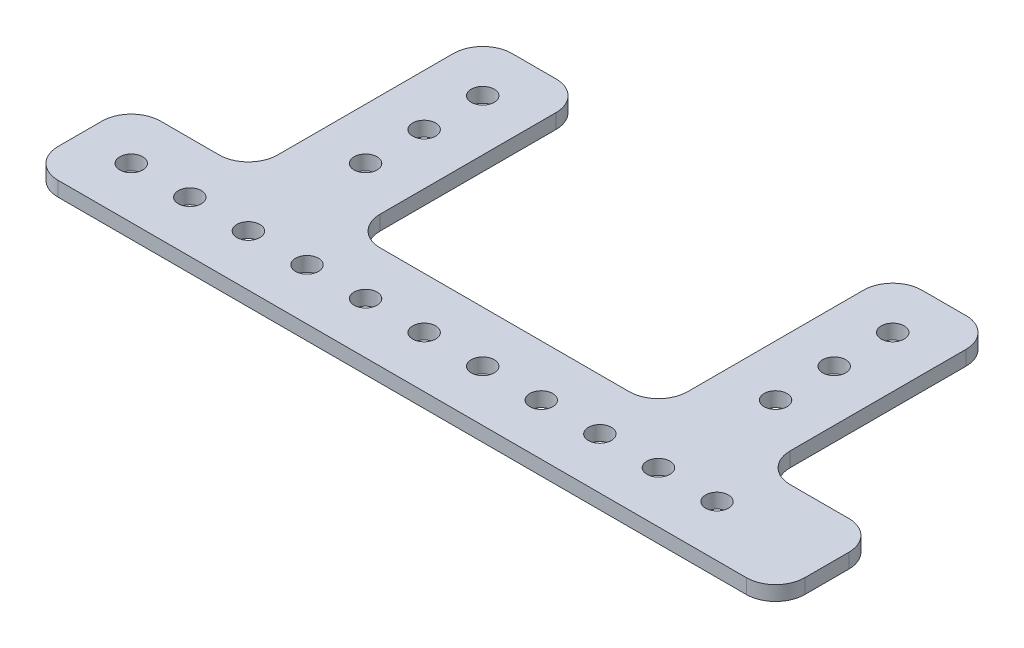
SolidWorks part; units mm, degrees
material "6061-T6 (SS)"
ref_plane "Front Plane" through (0, 0, 0) normal (0, 0, 1) x (1, 0, 0)
ref_plane "Top Plane" through (0, 0, 0) normal (0, 1, 0) x (1, 0, 0)
ref_plane "Right Plane" through (0, 0, 0) normal (1, 0, 0) x (0, 0, -1)
sketch "Sketch1" plane through (0, 0, 0) normal (0, 1, 0) x (1, 0, 0)
  line L0 (-82.55, 0) -> (82.55, 0)
  line L1 (82.55, 0) -> (82.55, 25.4)
  line L2 (82.55, 25.4) -> (57.15, 25.4)
  line L3 (57.15, 25.4) -> (57.15, 76.2)
  line L4 (57.15, 76.2) -> (31.75, 76.2)
  line L5 (31.75, 76.2) -> (31.75, 25.4)
  line L6 (31.75, 25.4) -> (-31.75, 25.4)
  line L7 (-31.75, 25.4) -> (-31.75, 76.2)
  line L8 (-31.75, 76.2) -> (-57.15, 76.2)
  line L9 (-57.15, 76.2) -> (-57.15, 25.4)
  line L10 (-57.15, 25.4) -> (-82.55, 25.4)
  line L11 (-82.55, 25.4) -> (-82.55, 0)
  line L12 (-82.55, 12.7) -> (82.55, 12.7) construction
  line L13 (-69.85, 12.7) -> (-57.15, 12.7) construction
  line L14 (-44.45, 76.2) -> (-44.45, 0) construction
  line L15 (-44.45, 38.1) -> (-44.45, 50.8) construction
  line L16 (0, 0) -> (0, 25.4) construction
  line L17 (-55.5625, 74.6125) -> (-55.5625, 23.8125)
  line L18 (-55.5625, 23.8125) -> (-80.9625, 23.8125)
  line L19 (-80.9625, 23.8125) -> (-80.9625, 1.5875)
  line L20 (-80.9625, 1.5875) -> (80.9625, 1.5875)
  line L21 (80.9625, 1.5875) -> (80.9625, 23.8125)
  line L22 (80.9625, 23.8125) -> (55.5625, 23.8125)
  line L23 (55.5625, 23.8125) -> (55.5625, 74.6125)
  line L24 (55.5625, 74.6125) -> (33.3375, 74.6125)
  line L25 (33.3375, 74.6125) -> (33.3375, 23.8125)
  line L26 (33.3375, 23.8125) -> (-33.3375, 23.8125)
  line L27 (-33.3375, 23.8125) -> (-33.3375, 74.6125)
  line L28 (-33.3375, 74.6125) -> (-55.5625, 74.6125)
  circle A0 centre (-69.85, 12.7) radius 2.4892
  circle A1 centre (-57.15, 12.7) radius 2.4892
  circle A2 centre (-44.45, 12.7) radius 2.4892
  circle A3 centre (-31.75, 12.7) radius 2.4892
  circle A4 centre (-19.05, 12.7) radius 2.4892
  circle A5 centre (-6.35, 12.7) radius 2.4892
  circle A6 centre (6.35, 12.7) radius 2.4892
  circle A7 centre (19.05, 12.7) radius 2.4892
  circle A8 centre (31.75, 12.7) radius 2.4892
  circle A9 centre (44.45, 12.7) radius 2.4892
  circle A10 centre (57.15, 12.7) radius 2.4892
  circle A11 centre (-44.45, 38.1) radius 2.4892
  circle A12 centre (-44.45, 50.8) radius 2.4892
  circle A13 centre (-44.45, 63.5) radius 2.4892
  circle A14 centre (44.45, 38.1) radius 2.4892
  circle A15 centre (44.45, 50.8) radius 2.4892
  circle A16 centre (44.45, 63.5) radius 2.4892
  point P15 (0, 0)
  dimension "D9" = 4.9784
  dimension "D1" = 63.5
  dimension "D2" = 25.4
  dimension "D3" = 25.4
  dimension "D4" = 25.4
  dimension "D5" = 25.4
  dimension "D6" = 25.4
  dimension "D7" = 50.8
  dimension "D8" = 12.7
  dimension "D11" = 12.7
  dimension "D12" = 12.7
  dimension "D14" = 12.7
  dimension "D15" = 1.5875
  dimension "D10" = 11
  dimension "D13" = 3
extrude "Boss-Extrude1" add sketch "Sketch1" along normal mid plane 3.175 contours L27 L28 L17 L18 L19 L20 L21 L22 L23 L24 L25 L26 A15 A0 A1 A2 A3 A4 A5 A6 A7 A8 A9 A10 A11 A12 A13 A14 A16
fillet "Fillet1" radius 6.35 12 edges at (-33.3375, 0, -23.8125) (33.3375, 0, -23.8125) (33.3375, 0, -74.6125) (55.5625, 0, -23.8125) (80.9625, 0, -23.8125) (80.9625, 0, -1.5875) (-80.9625, 0, -1.5875) (-80.9625, 0, -23.8125) (-55.5625, 0, -23.8125) (-55.5625, 0, -74.6125) (-33.3375, 0, -74.6125) (55.5625, 0, -74.6125)
